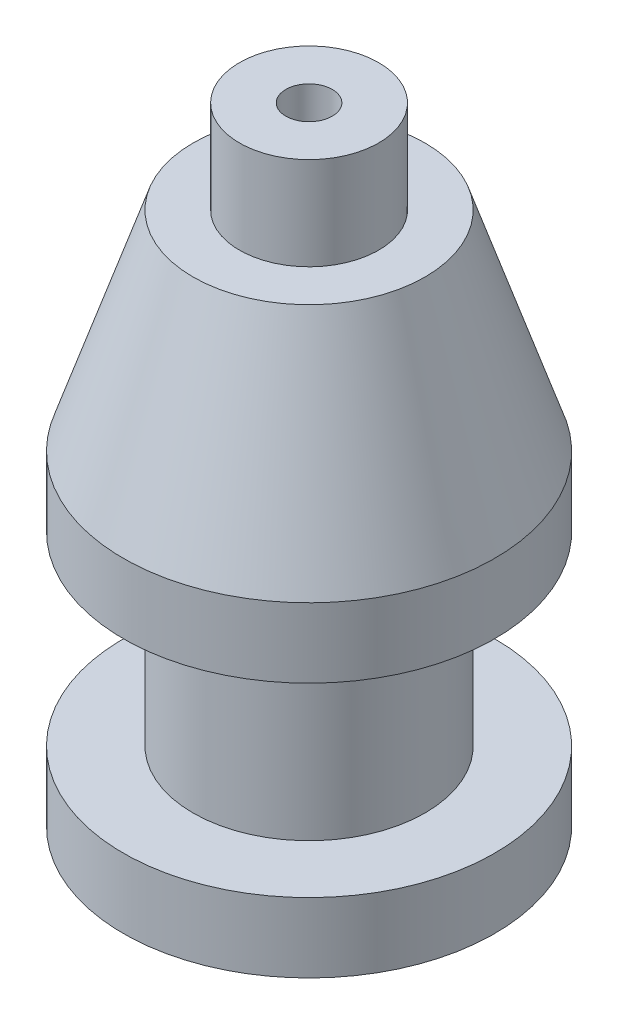
SolidWorks part; units mm, degrees
ref_plane "Front Plane" through (0, 0, 0) normal (0, 0, 1) x (1, 0, 0)
ref_plane "Top Plane" through (0, 0, 0) normal (0, 1, 0) x (1, 0, 0)
ref_plane "Right Plane" through (0, 0, 0) normal (1, 0, 0) x (0, 0, -1)
sketch "Sketch1" plane through (0, 0, 0) normal (0, 0, 1) x (1, 0, 0)
  line L0 (0, 0) -> (99672.2066, 0) construction
  line L1 (0, 0) -> (0, 99672.2066) construction
  line L2 (10, 270) -> (10, 0)
  line L3 (10, 0) -> (80, 0)
  line L4 (80, 0) -> (80, 30)
  line L5 (80, 30) -> (50, 30)
  line L6 (50, 30) -> (50, 110)
  line L7 (50, 110) -> (80, 110)
  line L8 (80, 110) -> (80, 140)
  line L9 (80, 140) -> (50, 230)
  line L10 (50, 230) -> (30, 230)
  line L11 (30, 230) -> (30, 270)
  line L12 (30, 270) -> (10, 270)
  point P7 (80, 123.3986)
  dimension "D1" = 160
  dimension "D2" = 100
  dimension "D3" = 100
  dimension "D4" = 60
  dimension "D5" = 20
  dimension "D6" = 40
  dimension "D7" = 230
  dimension "D8" = 80
  dimension "D9" = 30
  dimension "D10" = 30
revolve "Revolve1" add sketch "Sketch1" angle 360 about L1
